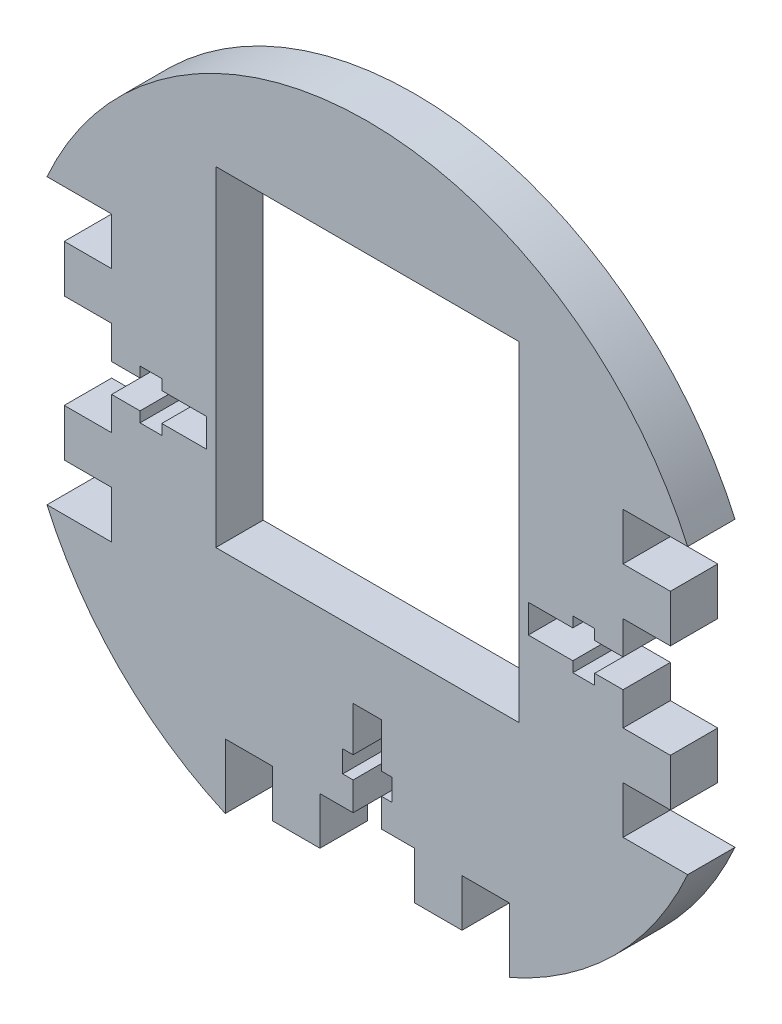
SolidWorks part; units mm, degrees
ref_plane "Front Plane" through (0, 0, 0) normal (0, 0, 1) x (1, 0, 0)
ref_plane "Top Plane" through (0, 0, 0) normal (0, 1, 0) x (1, 0, 0)
ref_plane "Right Plane" through (0, 0, 0) normal (1, 0, 0) x (0, 0, -1)
sketch "Sketch1" plane through (0, 0, 0) normal (0, 0, 1) x (1, 0, 0)
  line L0 (0, 0) -> (0, 49.2304) construction
  line L1 (-27, 50.3672) -> (-27, -45.8334) construction
  line L2 (27, -45.8334) -> (27, 50.3672) construction
  line L3 (-37, 0) -> (37, 0) construction
  line L4 (-48.5857, 15) -> (48.7516, 15) construction
  line L5 (50.4568, -15) -> (-48.5857, -15) construction
  line L6 (-27, 10) -> (-27, 15)
  line L7 (-27, 15) -> (-33.8231, 15)
  line L8 (-33.8231, -15) -> (-27, -15)
  line L9 (-27, -15) -> (-27, -10)
  line L10 (27, -10) -> (27, -15)
  line L11 (27, -15) -> (33.8231, -15)
  line L12 (33.8231, 15) -> (27, 15)
  line L13 (27, 15) -> (27, 10)
  line L14 (27, 0) -> (15.7792, 0) construction
  line L15 (27, -1.5) -> (27, -5)
  line L16 (32, -5) -> (32, -10)
  line L17 (32, -10) -> (27, -10)
  line L18 (32, -5) -> (27, -5)
  line L19 (27, 1.5) -> (27, 5)
  line L20 (27, 5) -> (32, 5)
  line L21 (32, 5) -> (32, 10)
  line L22 (32, 10) -> (27, 10)
  line L23 (27, -1.5) -> (27, 1.5) construction
  line L24 (27, 1.5) -> (24, 1.5)
  line L25 (21.7, 1.5) -> (21.7, 2.6)
  line L26 (24, -2.6) -> (21.7, -2.6)
  line L27 (24, 2.6) -> (24, 1.5)
  line L28 (21.7, 1.5) -> (17, 1.5)
  line L29 (17, 1.5) -> (17, -1.5)
  line L30 (17, -1.5) -> (21.7, -1.5)
  line L31 (24, -1.5) -> (24, -2.6)
  line L32 (21.7, 2.6) -> (24, 2.6)
  line L33 (21.7, -2.6) -> (21.7, -1.5)
  line L34 (24, -1.5) -> (27, -1.5)
  line L35 (17, 0) -> (27, 0) construction
  line L36 (-27, 0) -> (-15.7792, 0) construction
  line L37 (-27, 1.5) -> (-27, 5)
  line L38 (-32, 5) -> (-32, 10)
  line L39 (-32, 10) -> (-27, 10)
  line L40 (-32, 5) -> (-27, 5)
  line L41 (-27, -1.5) -> (-27, -5)
  line L42 (-27, -5) -> (-32, -5)
  line L43 (-32, -5) -> (-32, -10)
  line L44 (-32, -10) -> (-27, -10)
  line L45 (-27, 1.5) -> (-27, -1.5) construction
  line L46 (-27, -1.5) -> (-24, -1.5)
  line L47 (-21.7, -1.5) -> (-21.7, -2.6)
  line L48 (-24, 2.6) -> (-21.7, 2.6)
  line L49 (-24, -2.6) -> (-24, -1.5)
  line L50 (-21.7, -1.5) -> (-17, -1.5)
  line L51 (-17, -1.5) -> (-17, 1.5)
  line L52 (-17, 1.5) -> (-21.7, 1.5)
  line L53 (-24, 1.5) -> (-24, 2.6)
  line L54 (-21.7, -2.6) -> (-24, -2.6)
  line L55 (-21.7, 2.6) -> (-21.7, 1.5)
  line L56 (-24, 1.5) -> (-27, 1.5)
  line L57 (-17, 0) -> (-27, 0) construction
  line L58 (-16, 24.84) -> (-16, -23.5612) construction
  line L59 (-16, -23.5612) -> (16, -23.5612) construction
  line L60 (16, -23.5612) -> (16, 24.84) construction
  line L61 (16, 24.84) -> (-16, 24.84) construction
  line L62 (-27, -27) -> (27, -27) construction
  line L63 (-16, 24.84) -> (16, 24.84)
  line L64 (-16, 24.84) -> (-16, -10)
  line L65 (-16, -10) -> (16, -10)
  line L66 (16, 24.84) -> (16, -10)
  line L67 (-10, -27) -> (-15, -27)
  line L68 (-15, -27) -> (-15, -33.8231)
  line L69 (10, -27) -> (15, -27)
  line L70 (15, -27) -> (15, -33.8231)
  line L71 (0, -27) -> (0, -15.7792) construction
  line L72 (-1.5, -27) -> (-5, -27)
  line L73 (-5, -32) -> (-10, -32)
  line L74 (-10, -32) -> (-10, -27)
  line L75 (-5, -32) -> (-5, -27)
  line L76 (1.5, -27) -> (5, -27)
  line L77 (5, -27) -> (5, -32)
  line L78 (5, -32) -> (10, -32)
  line L79 (10, -32) -> (10, -27)
  line L80 (-1.5, -27) -> (1.5, -27) construction
  line L81 (1.5, -27) -> (1.5, -24)
  line L82 (1.5, -21.7) -> (2.6, -21.7)
  line L83 (-2.6, -24) -> (-2.6, -21.7)
  line L84 (2.6, -24) -> (1.5, -24)
  line L85 (1.5, -21.7) -> (1.5, -17)
  line L86 (1.5, -17) -> (-1.5, -17)
  line L87 (-1.5, -17) -> (-1.5, -21.7)
  line L88 (-1.5, -24) -> (-2.6, -24)
  line L89 (2.6, -21.7) -> (2.6, -24)
  line L90 (-2.6, -21.7) -> (-1.5, -21.7)
  line L91 (-1.5, -24) -> (-1.5, -27)
  line L92 (0, -17) -> (0, -27) construction
  circle A0 centre (0, 0) radius 37 construction
  arc A1 (-33.8231, 15) -> (33.8231, 15) centre (0, 0) cw
  arc A3 (-15, -33.8231) -> (-33.8231, -15) centre (0, 0) cw
  arc A4 (15, -33.8231) -> (33.8231, -15) centre (0, 0) ccw
  dimension "D1" = 74
  dimension "D2" = 54
  dimension "D3" = 30
  dimension "D4" = 10
  dimension "D5" = 5
  dimension "D6" = 5
  dimension "D7" = 5.2
  dimension "D8" = 3
  dimension "D9" = 2.3
  dimension "D10" = 3
  dimension "D11" = 10
  dimension "D12" = 10
  dimension "D13" = 5
  dimension "D14" = 5
  dimension "D15" = 5.2
  dimension "D16" = 3
  dimension "D17" = 2.3
  dimension "D18" = 3
  dimension "D19" = 10
  dimension "D20" = 32
  dimension "D21" = 27
  dimension "D22" = 30
  dimension "D23" = 10
  dimension "D24" = 5
  dimension "D25" = 5
  dimension "D26" = 5.2
  dimension "D27" = 3
  dimension "D28" = 2.3
  dimension "D29" = 3
  dimension "D30" = 10
extrude "Boss-Extrude1" add sketch "Sketch1" along normal blind 5
